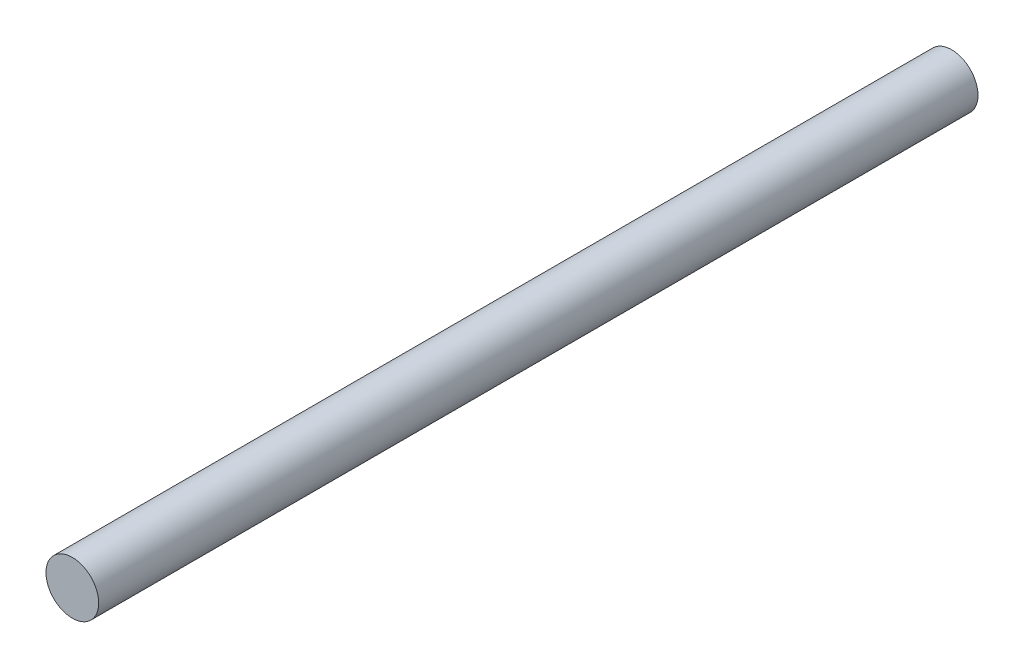
SolidWorks part; units mm, degrees
ref_plane "前视基准面" through (0, 0, 0) normal (0, 0, 1) x (1, 0, 0)
ref_plane "上视基准面" through (0, 0, 0) normal (0, 1, 0) x (1, 0, 0)
ref_plane "右视基准面" through (0, 0, 0) normal (1, 0, 0) x (0, 0, -1)
sketch "草图1" plane through (0, 0, 0) normal (0, 0, 1) x (1, 0, 0)
  circle A0 centre (0, 0) radius 6
  dimension "D1" = 12
extrude "凸台-拉伸1" add sketch "草图1" along normal blind 200
